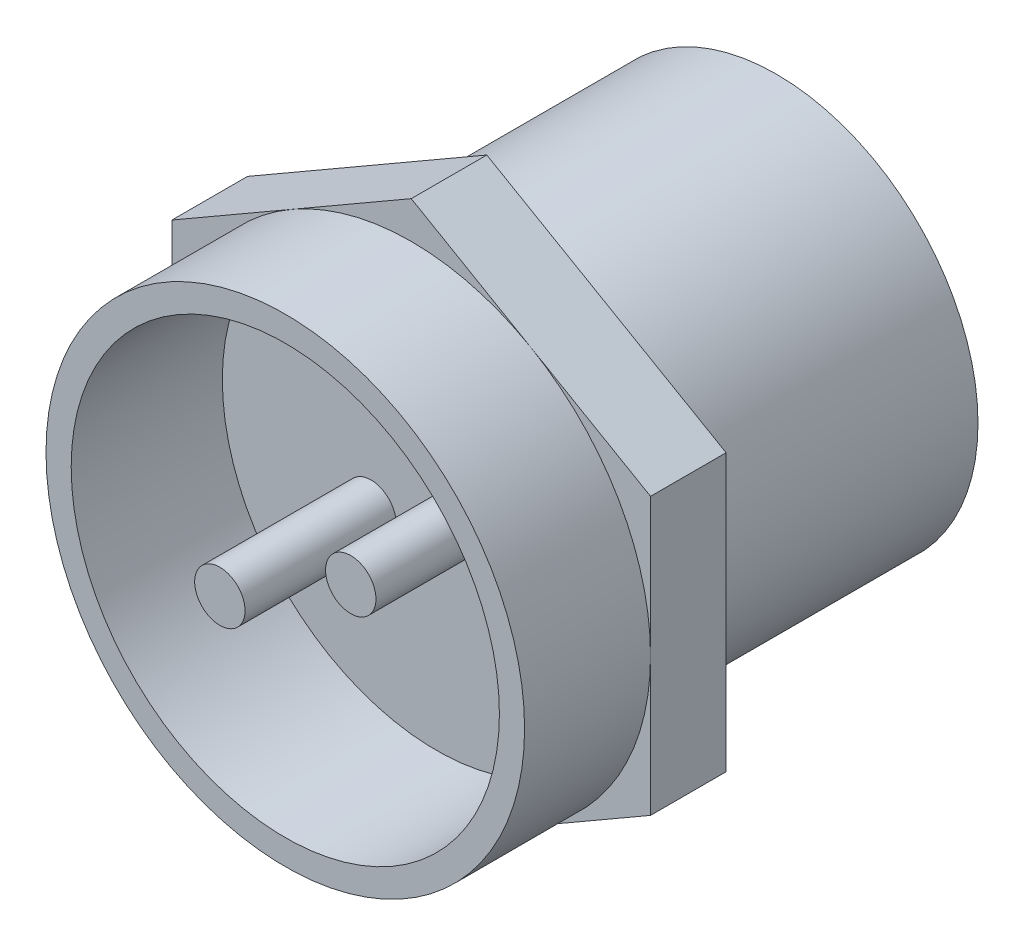
SolidWorks part; units mm, degrees
ref_plane "前视基准面" through (0, 0, 0) normal (0, 0, 1) x (1, 0, 0)
ref_plane "上视基准面" through (0, 0, 0) normal (0, 1, 0) x (1, 0, 0)
ref_plane "右视基准面" through (0, 0, 0) normal (1, 0, 0) x (0, 0, -1)
sketch "草图1" plane through (0, 0, 0) normal (0, 0, 1) x (1, 0, 0)
  circle A0 centre (0, 0) radius 9.5
extrude "凸台-拉伸1" add sketch "草图1" along normal blind 5
sketch "草图2" plane through (0, 0, 0) normal (0, 0, -1) x (-1, 0, 0)
  circle A0 centre (0, 0) radius 8
extrude "凸台-拉伸2" add sketch "草图2" along normal blind 11.5
sketch "草图3" plane through (0, 0, 0) normal (0, 0, -1) x (-1, 0, 0)
  line L1 (0, 10.9697) -> (-9.5, 5.4848)
  line L2 (-9.5, 5.4848) -> (-9.5, -5.4848)
  line L3 (-9.5, -5.4848) -> (0, -10.9697)
  line L4 (0, -10.9697) -> (9.5, -5.4848)
  line L5 (9.5, -5.4848) -> (9.5, 5.4848)
  line L6 (9.5, 5.4848) -> (0, 10.9697)
  circle A0 centre (0, 0) radius 9.5 construction
extrude "凸台-拉伸3" add sketch "草图3" against normal blind 3
sketch "草图4" plane through (0, 0, 5) normal (0, 0, 1) x (1, 0, 0)
  circle A0 centre (0, 0) radius 9.5
extrude "凸台-拉伸4" add sketch "草图4" along normal blind 3
sketch "草图5" plane through (0, 0, 8) normal (0, 0, 1) x (1, 0, 0)
  line L0 (0, -10.9697) -> (9.5, -5.4848)
  line L1 (9.5, -5.4848) -> (4.75, -8.2272) construction
  circle A0 centre (0, 0) radius 8.5
  circle A1 centre (2.5981, 1.5) radius 1
  circle A2 centre (-2.5981, -1.5) radius 1
extrude "切除-拉伸2" cut sketch "草图5" against normal blind 6 contours A0 A1 A2
